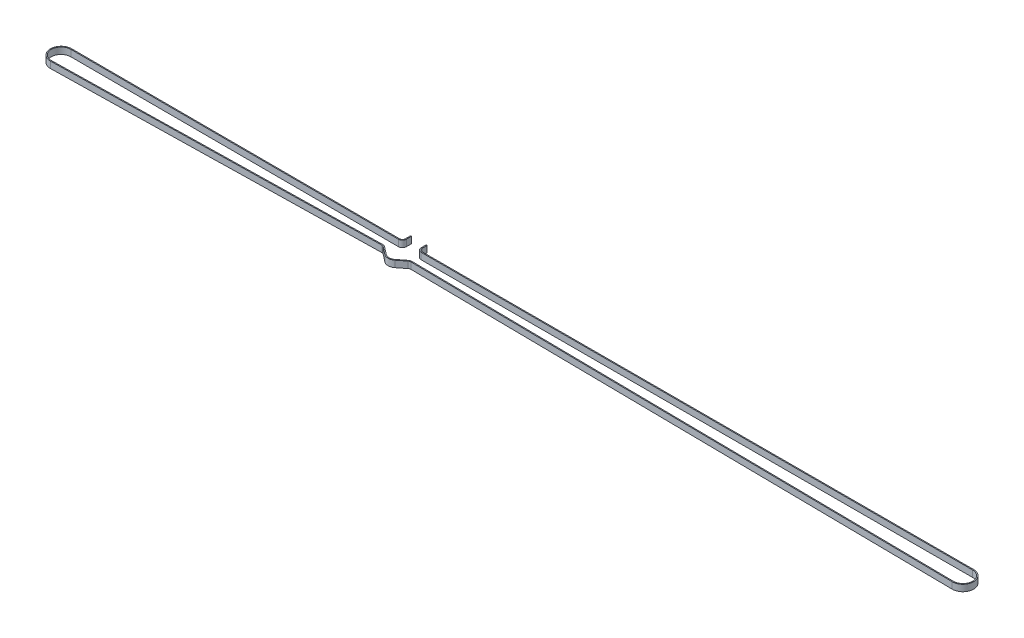
SolidWorks part; units mm, degrees
ref_plane "Front Plane" through (0, 0, 0) normal (0, 0, 1) x (1, 0, 0)
ref_plane "Top Plane" through (0, 0, 0) normal (0, 1, 0) x (1, 0, 0)
ref_plane "Right Plane" through (0, 0, 0) normal (1, 0, 0) x (0, 0, -1)
sketch "Sketch1" plane through (0, 0, 0) normal (0, 1, 0) x (1, 0, 0)
  line L0 (-697, 0) -> (697, 0) construction
  line L1 (-183.4, 20) -> (-183.4, 14) construction
  line L2 (-183.4, 20) -> (-183.4, 14) construction
  line L3 (-160.6, 14) -> (-160.6, 20) construction
  line L4 (-160.6, 14) -> (-160.6, 20) construction
  line L5 (-696.7072, -14.9971) -> (-194.5269, -5.1921)
  line L6 (-190.3938, -6.5723) -> (-178.7797, -15.6623)
  line L7 (-183.4, 28) -> (-183.4, 20)
  line L8 (-165.2203, -15.6623) -> (-153.6062, -6.5723)
  line L9 (-149.5247, -5.1913) -> (696.8262, -14.999)
  line L10 (-189.4118, 14) -> (-696.9704, 15)
  line L11 (-183.4, 14) -> (-189.4118, 14) construction
  line L12 (-160.6, 28) -> (-160.6, 20)
  line L13 (-154.5929, 14) -> (696.9824, 15)
  line L14 (-160.6, 14) -> (-154.5929, 14) construction
  line L15 (-183.4, 28) -> (-160.6, 28) construction
  line L16 (-194.4, -11.6909) -> (-149.6, -11.6909) construction
  line L17 (-172, -7) -> (-172, -11.6909) construction
  arc A0 (-696.9704, 15) -> (-696.7072, -14.9971) centre (-697, 0) ccw
  arc A1 (696.8262, -14.999) -> (696.9824, 15) centre (697, 0) ccw
  circle A4 centre (-172, -7) radius 13.02 construction
  arc A5 (-178.7797, -15.6623) -> (-165.2203, -15.6623) centre (-172, -7) ccw
  circle A6 centre (-149.6, -11.6909) radius 5 construction
  circle A7 centre (-194.4, -11.6909) radius 5 construction
  arc A8 (-190.3938, -6.5723) -> (-194.5269, -5.1921) centre (-194.4, -11.6909) ccw
  arc A9 (-149.5247, -5.1913) -> (-153.6062, -6.5723) centre (-149.6, -11.6909) ccw
  arc A10 (-183.4, 20) -> (-189.4118, 14) centre (-189.4, 20) cw
  arc A11 (-160.6, 20) -> (-154.5929, 14) centre (-154.6, 20) ccw
  point P4 (-194.4, -11.6909)
  point P10 (-149.6, -11.6909)
  point P12 (-172, -7)
  dimension "D1" = 30
  dimension "D3" = 22
  dimension "D4" = 10
  dimension "D5" = 1.5
  dimension "D2" = 1394
  dimension "D6" = 8
  dimension "D7" = 44.8
  dimension "D8" = 9.3818
extrude "Extrude-Thin1" add sketch "Sketch1" along normal mid plane 10 thin
